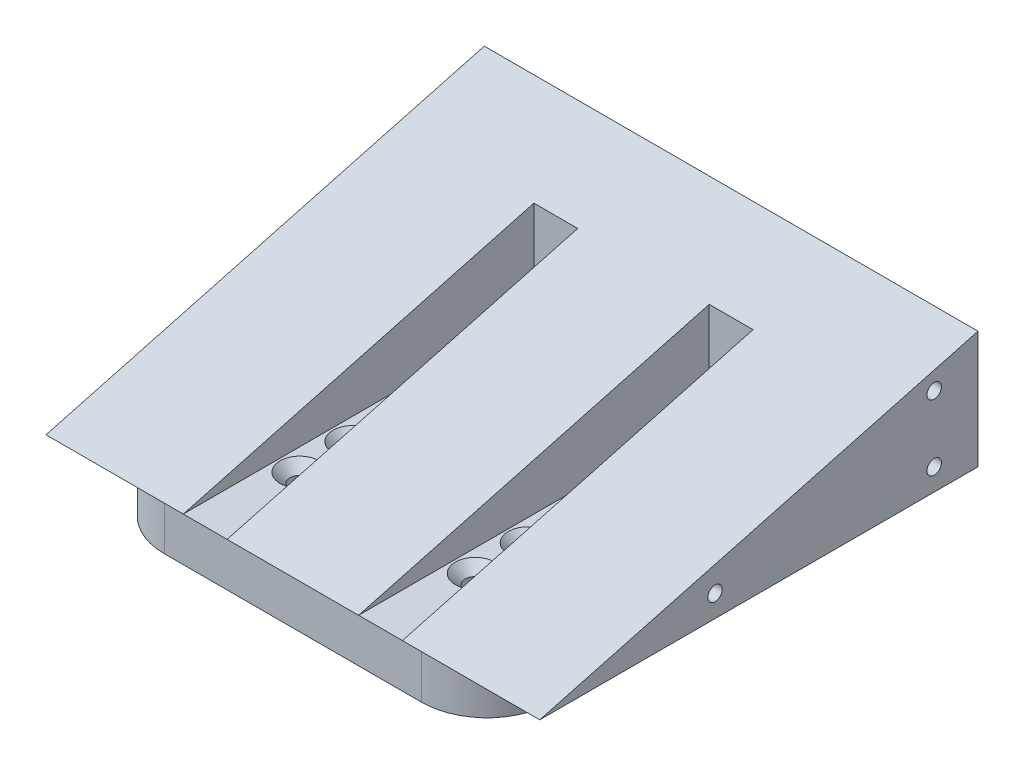
SolidWorks part; units mm, degrees
ref_plane "Front Plane" through (0, 0, 0) normal (0, 0, 1) x (1, 0, 0)
ref_plane "Top Plane" through (0, 0, 0) normal (0, 1, 0) x (1, 0, 0)
ref_plane "Right Plane" through (0, 0, 0) normal (1, 0, 0) x (0, 0, -1)
sketch "Sketch1" plane through (0, 0, 0) normal (1, 0, 0) x (0, 0, -1)
  line L0 (-50, 0) -> (50, 0)
  line L1 (-87.3205, 0) -> (83.6484, 45.811)
  line L2 (-50, 0) -> (-50, 10)
  line L3 (50, 0) -> (50, 36.7949)
  line L4 (83.6484, 45.811) -> (97.8834, -7.3149)
  line L5 (-87.3205, 0) -> (83.6484, 0)
  line L6 (83.6484, 0) -> (83.6484, 45.811)
  point P5 (0, 0)
  dimension "D1" = 15
  dimension "D2" = 177
  dimension "D3" = 10
  dimension "D4" = 100
  dimension "D5" = 55
  dimension "D6" = 170.9689
extrude "Boss-Extrude1" add sketch "Sketch1" along normal blind 112.65 contours L0 L3 L1 L2
hole_wizard "M4x0.7 Tapped Hole1" positions "Sketch4" profile "Sketch5" tap size "M4x0.7" standard "ANSI Metric"
sketch "Sketch4" plane through (112.65, 0, 0) normal (1, 0, 0) x (0, 0, -1)
  line L0 (-50, 0) -> (-50, 10) construction
  point P0 (-10, 15)
  point P2 (40, 15)
  point P5 (40, 30)
  dimension "D1" = 15
  dimension "D2" = 10
  dimension "D3" = 15
  dimension "D4" = 40
sketch "Sketch5" plane through (112.65, 15, 10) normal (0, 1, 0) x (0, 0, -1)
  line L0 (0, 0) -> (0, 11.0914)
  line L1 (0, 11.0914) -> (1.65, 10.1)
  line L2 (1.65, 10.1) -> (1.65, 0)
  line L5 (1.65, 0) -> (0, 0)
  line L10 (0, 11.0914) -> (-1.65, 10.1) construction
  line L11 (0, -6.35) -> (0, 107.95) construction
  dimension "Tap Drill Dia." = 3.3
  dimension "Tap Drill Depth" = 10.1
  dimension "Drill Angle" = 118
cosmetic thread "Hole Thread1" parameters "D1"=8, "D2"=4
cosmetic thread "Hole Thread2" parameters "D1"=8, "D2"=4
cosmetic thread "Hole Thread3" parameters "D1"=8, "D2"=4
sketch "Sketch7" plane through (0, 0, 50) normal (0, 0, 1) x (1, 0, 0)
  line L0 (112.65, 10) -> (66.325, 10) construction
  line L1 (71.325, 64.4527) -> (81.325, 64.4527)
  line L2 (71.325, 64.4527) -> (71.325, 10)
  line L3 (71.325, 10) -> (81.325, 10)
  line L4 (81.325, 64.4527) -> (81.325, 10)
  line L5 (71.325, 64.4527) -> (81.325, 10) construction
  line L6 (71.325, 10) -> (81.325, 64.4527) construction
  line L8 (112.65, 36.7949) -> (0, 36.7949) construction
  point P0 (76.325, 37.2263)
  point P10 (56.325, 36.7949)
  dimension "D1" = 10
  dimension "D2" = 20
extrude "Cut-Extrude2" cut sketch "Sketch7" against normal blind 80
hole_wizard "CSK for M4 SFHCS1" positions "Sketch8" profile "Sketch10" countersink size "M4" standard "ANSI Metric"
sketch "Sketch8" plane through (0, 10, 0) normal (0, 1, 0) x (1, 0, 0)
  point P0 (76.325, 11.56)
  point P2 (76.325, -28.44)
  point P10 (76.325, -16.36)
  point P12 (76.325, 23.64)
  point P15 (0, 0)
  dimension "D1" = 40
  dimension "D2" = 21.56
  dimension "D3" = 5
  dimension "D4" = 12.08
  dimension "D5" = 40
sketch "Sketch10" plane through (76.325, 10, -11.56) normal (1, 0, 0) x (0, 0, 1)
  line L0 (0, 0) -> (0, 11.4519)
  line L1 (0, 11.4519) -> (2.25, 10.1)
  line L2 (2.25, 10.1) -> (2.25, 2.23)
  line L3 (2.25, 2.23) -> (4.48, 0)
  line L5 (4.48, 0) -> (0, 0)
  line L6 (-2.25, 2.23) -> (-4.48, 0) construction
  line L10 (0, 11.4519) -> (-2.25, 10.1) construction
  line L11 (0, -6.35) -> (0, 107.95) construction
  dimension "Hole Dia." = 4.5
  dimension "Hole Depth" = 10.1
  dimension "Near C'Sink Dia." = 8.96
  dimension "Near C'Sink Angle" = 90
  dimension "Drill Angle" = 118
sketch "Sketch11" plane through (0, 0, 50) normal (0, 0, 1) x (1, 0, 0)
  line L0 (112.65, 10) -> (81.325, 10) construction
  line L1 (112.65, 0) -> (100.65, 0)
  line L2 (112.65, 0) -> (112.65, 10)
  line L3 (112.65, 10) -> (100.65, 10)
  line L4 (100.65, 0) -> (100.65, 10)
  dimension "D1" = 12
extrude "Cut-Extrude3" cut sketch "Sketch11" against normal through all
ref_plane "Plane1" through (56.325, 0, 0) normal (-1, 0, 0) x (0, 0, 1)
mirror "Mirror1" about plane through (56.325, 0, 0) normal (-1, 0, 0) of "Cut-Extrude3", "M4x0.7 Tapped Hole1", "CSK for M4 SFHCS1", "Cut-Extrude2"
cosmetic thread "Hole Thread4" parameters "D1"=8, "D2"=4
cosmetic thread "Hole Thread5" parameters "D1"=8, "D2"=4
cosmetic thread "Hole Thread6" parameters "D1"=8, "D2"=4
fillet "Fillet1" radius 15 4 edges at (100.65, 5, 50) (100.65, 5, -50) (12, 5, -50) (12, 5, 50)
